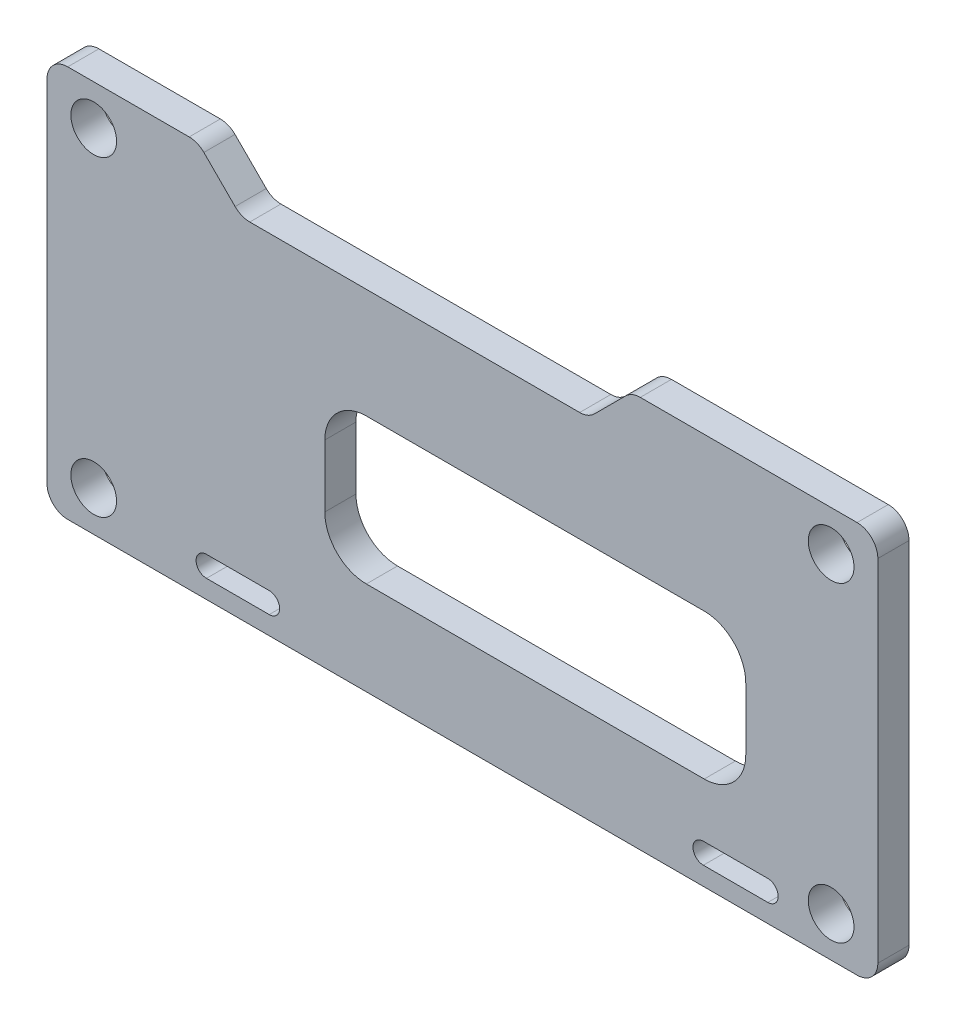
SolidWorks part; units mm, degrees
material "ABS"
ref_plane "前视基准面" through (0, 0, 0) normal (0, 0, 1) x (1, 0, 0)
ref_plane "上视基准面" through (0, 0, 0) normal (0, 1, 0) x (1, 0, 0)
ref_plane "右视基准面" through (0, 0, 0) normal (1, 0, 0) x (0, 0, -1)
sketch "草图1" plane through (0, 0, 0) normal (0, 0, 1) x (1, 0, 0)
  line L1 (-21.7384, 9.901) -> (13.7616, 9.901) construction
  line L2 (-21.7384, 9.901) -> (-21.7384, -5.099) construction
  line L3 (-21.7384, -5.099) -> (13.7616, -5.099) construction
  line L4 (13.7616, 9.901) -> (13.7616, -5.099) construction
  line L5 (-21.7384, 9.901) -> (13.7616, -5.099) construction
  line L6 (-21.7384, -5.099) -> (13.7616, 9.901) construction
  line L7 (-23.9884, 11.8368) -> (16.0116, 11.8368)
  line L8 (-23.9884, 11.8368) -> (-23.9884, -7.0348)
  line L9 (-23.9884, -7.0348) -> (16.0116, -7.0348)
  line L10 (16.0116, 11.8368) -> (16.0116, -7.0348)
  line L11 (-23.9884, 11.8368) -> (16.0116, -7.0348) construction
  line L12 (-23.9884, -7.0348) -> (16.0116, 11.8368) construction
  circle A0 centre (-21.7384, 9.901) radius 1.1
  circle A1 centre (-21.7384, -5.099) radius 1.1
  circle A2 centre (13.7616, -5.099) radius 1.1
  circle A3 centre (13.7616, 9.901) radius 1.1
  point P0 (-3.9884, 2.401)
  point P9 (-3.9884, 2.401)
  dimension "D3" = 40
  dimension "D1" = 15
  dimension "D2" = 35.5
extrude "凸台-拉伸1" add sketch "草图1" along normal blind 1.5
sketch "草图2" plane through (0, 0, 1.5) normal (0, 0, 1) x (1, 0, 0)
  line L0 (-16.7286, 11.8368) -> (-14.6398, 9.748)
  line L1 (16.0116, 11.8368) -> (-23.9884, 11.8368) construction
  line L2 (-14.6398, 9.748) -> (2.0715, 9.748)
  line L3 (2.0715, 9.748) -> (5.5197, 13.1963)
  line L4 (5.5197, 13.1963) -> (-14.8719, 13.1963)
  line L5 (-14.8719, 13.1963) -> (-16.7286, 11.8368)
  line L6 (-16.3104, -5.6502) -> (-13.2888, -5.6502) construction
  line L7 (-10.6138, 4.4657) -> (9.6518, 4.4657)
  line L8 (-10.6138, 4.4657) -> (-10.6138, -2.5364)
  line L9 (-10.6138, -2.5364) -> (9.6518, -2.5364)
  line L10 (9.6518, 4.4657) -> (9.6518, -2.5364)
  line L11 (-10.6138, 4.4657) -> (9.6518, -2.5364) construction
  line L12 (-10.6138, -2.5364) -> (9.6518, 4.4657) construction
  line L13 (-16.3104, -5.1502) -> (-13.2888, -5.1502)
  line L14 (-16.3104, -6.1502) -> (-13.2888, -6.1502)
  line L15 (7.6104, -5.6502) -> (10.7136, -5.6502) construction
  line L16 (7.6104, -5.1502) -> (10.7136, -5.1502)
  line L17 (7.6104, -6.1502) -> (10.7136, -6.1502)
  arc A0 (-16.3104, -5.1502) -> (-16.3104, -6.1502) centre (-16.3104, -5.6502) ccw
  arc A1 (-13.2888, -6.1502) -> (-13.2888, -5.1502) centre (-13.2888, -5.6502) ccw
  arc A2 (7.6104, -5.1502) -> (7.6104, -6.1502) centre (7.6104, -5.6502) ccw
  arc A3 (10.7136, -6.1502) -> (10.7136, -5.1502) centre (10.7136, -5.6502) ccw
  point P6 (0, 0)
  point P8 (-0.481, 0.9647)
  point P15 (-14.7996, -5.6502)
  point P20 (9.162, -5.6502)
  point P27 (9.162, -5.7611)
  point P28 (-16.3104, -5.6115)
  point P29 (-13.2888, -5.6502)
  dimension "D1" = 0.5
  dimension "D2" = 0.5
  dimension "D3" = 45
  dimension "D4" = 45
extrude "切除-拉伸1" cut sketch "草图2" against normal blind 1.5
fillet "圆角1" radius 1 4 edges at (4.1603, 11.8368, 0.75) (2.0715, 9.748, 0.75) (-14.6398, 9.748, 0.75) (-16.7286, 11.8368, 0.75)
fillet "圆角2" radius 1 4 edges at (16.0116, 11.8368, 0.75) (16.0116, -7.0348, 0.75) (-23.9884, -7.0348, 0.75) (-23.9884, 11.8368, 0.75)
fillet "圆角3" radius 2 4 edges at (9.6518, 4.4657, 0.75) (9.6518, -2.5364, 0.75) (-10.6138, -2.5364, 0.75) (-10.6138, 4.4657, 0.75)
